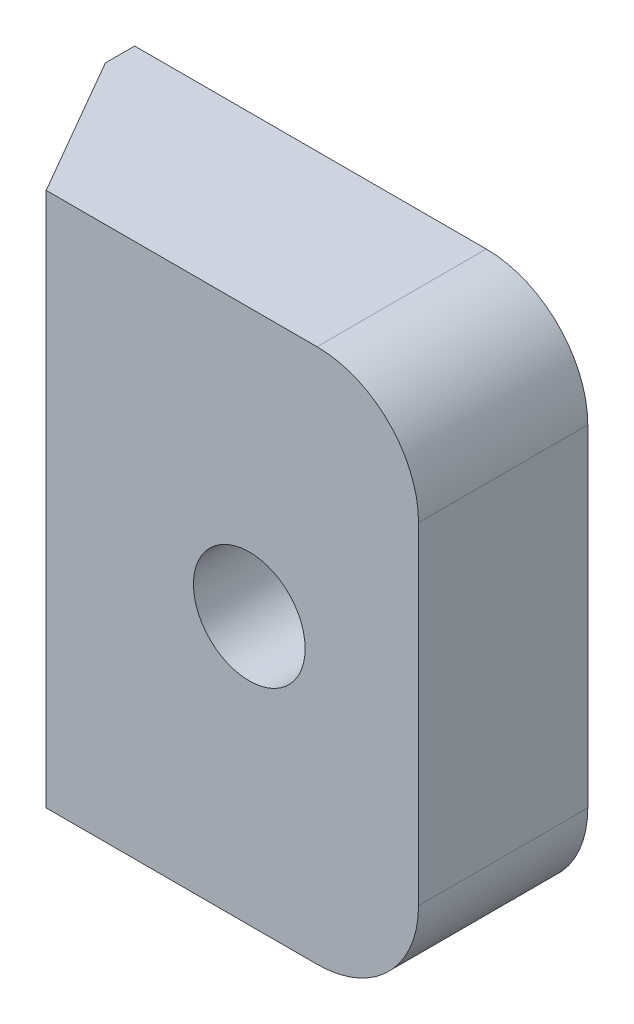
SolidWorks part; units mm, degrees
material "Сплав 2024"
ref_plane "Спереди" through (0, 0, 0) normal (0, 0, 1) x (1, 0, 0)
ref_plane "Сверху" through (0, 0, 0) normal (0, 1, 0) x (1, 0, 0)
ref_plane "Справа" through (0, 0, 0) normal (1, 0, 0) x (0, 0, -1)
sketch "Эскиз1" plane through (0, 0, 0) normal (0, 1, 0) x (1, 0, 0)
  line L0 (0, 0) -> (0, 5)
  line L1 (0, 5) -> (-13.8868, 5)
  line L2 (-13.8868, 5) -> (-11, 0)
  line L3 (-11, 0) -> (0, 0)
  dimension "D1" = 11
  dimension "D2" = 60
  dimension "D3" = 5
extrude "Бобышка-Вытянуть1" add sketch "Эскиз1" along normal blind 15.8
fillet "Скругление1" radius 3 2 edges at (0, 0, -2.5) (0, 15.8, -2.5)
sketch "Эскиз2" plane through (0, 0, 0) normal (0, 0, 1) x (1, 0, 0)
  line L0 (0, 7.9) -> (-7.9383, 7.9) construction
  line L1 (0, 12.8) -> (0, 3) construction
  point P4 (-5, 7.9)
  dimension "D1" = 5
hole_wizard "Отверстие обработанное метчиком M4x0.71" positions "Эскиз4" profile "Эскиз3" tap size "M4x0.7" standard "Ansi Metric" end condition through all
sketch "Эскиз4" plane through (0, 0, 0) normal (0, 0, 1) x (1, 0, 0)
  point P0 (-5, 7.9)
sketch "Эскиз3" plane through (-5, 7.9, 0) normal (1, 0, 0) x (0, -1, 0)
  line L0 (0, 0) -> (0, 5)
  line L1 (0, 5) -> (1.65, 5)
  line L2 (1.65, 5) -> (1.65, 0)
  line L5 (1.65, 0) -> (0, 0)
  line L11 (0, -6.35) -> (0, 107.95) construction
  dimension "Диаметр резьбы" = 3.3
  dimension "Глубина проходного сверла" = 5
chamfer "Фаска1" distance 0.5 angle 90 1 edges at (-13.8868, 7.9, -5)
